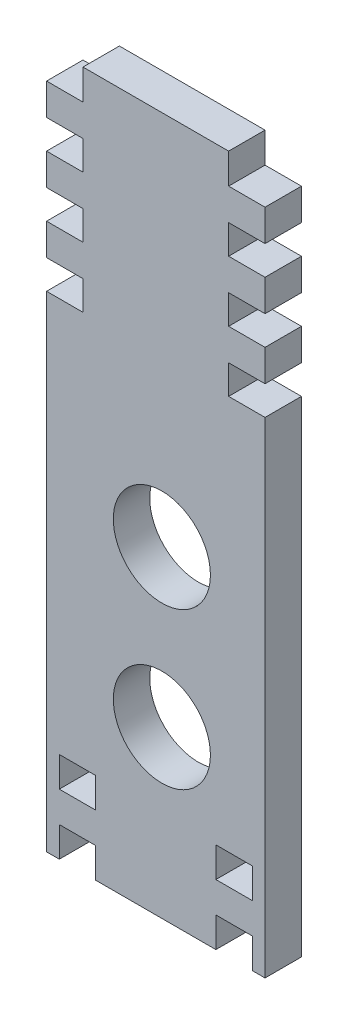
SolidWorks part; units mm, degrees
ref_plane "Plan de face" through (0, 0, 0) normal (0, 0, 1) x (1, 0, 0)
ref_plane "Plan de dessus" through (0, 0, 0) normal (0, 1, 0) x (1, 0, 0)
ref_plane "Plan de droite" through (0, 0, 0) normal (1, 0, 0) x (0, 0, -1)
sketch "Esquisse1" plane through (0, 0, 0) normal (0, 0, 1) x (1, 0, 0)
  line L0 (-12, 0) -> (12, 0)
  line L1 (12, 0) -> (12, -0.2)
  line L2 (12, -5) -> (18, -5)
  line L3 (18, -5) -> (18, -10.2)
  line L4 (18, -10.2) -> (12, -10.2)
  line L5 (12, -0.2) -> (12, -5)
  line L6 (0, 0) -> (0, -26.7853) construction
  line L7 (12, -10.2) -> (12, -15)
  line L8 (12, -15) -> (18, -15)
  line L9 (18, -15) -> (18, -20.2)
  line L10 (18, -20.2) -> (12, -20.2)
  line L11 (12, -20.2) -> (12, -25)
  line L12 (12, -25) -> (18, -25)
  line L13 (18, -25) -> (18, -30.2)
  line L14 (18, -30.2) -> (12, -30.2)
  line L15 (12, -30.2) -> (12, -35)
  line L16 (12, -35) -> (18, -35)
  line L22 (-12, -35) -> (-18, -35)
  line L23 (-12, -30.2) -> (-12, -35)
  line L24 (-18, -30.2) -> (-12, -30.2)
  line L25 (-18, -25) -> (-18, -30.2)
  line L26 (-12, -25) -> (-18, -25)
  line L27 (-12, -20.2) -> (-12, -25)
  line L28 (-18, -20.2) -> (-12, -20.2)
  line L29 (-18, -15) -> (-18, -20.2)
  line L30 (-12, -15) -> (-18, -15)
  line L31 (-12, -10.2) -> (-12, -15)
  line L32 (-12, -0.2) -> (-12, -5)
  line L33 (-18, -10.2) -> (-12, -10.2)
  line L34 (-18, -5) -> (-18, -10.2)
  line L35 (-12, -5) -> (-18, -5)
  line L36 (-12, 0) -> (-12, -0.2)
  line L46 (-18, -35) -> (-18, -115)
  line L47 (18, -40.2) -> (12, -40.2) [skipped]
  line L48 (-18, -115) -> (-15.9, -115)
  line L49 (18, -115) -> (18, -35)
  line L50 (0, -65) -> (0, 28.2086) construction
  line L51 (-15.9, -100.05) -> (-9.9, -100.05)
  line L52 (-15.9, -100.05) -> (-15.9, -105)
  line L53 (18, -35) -> (18, -40.2) [skipped]
  line L54 (-15.9, -105) -> (-9.9, -105)
  line L55 (-9.9, -100.05) -> (-9.9, -105)
  line L56 (-15.9, -110.05) -> (-9.9, -110.05)
  line L57 (-15.9, -110.05) -> (-15.9, -115)
  line L59 (-9.9, -110.05) -> (-9.9, -115)
  line L60 (-9.9, -115) -> (9.9, -115)
  line L61 (15.9, -110.05) -> (15.9, -115)
  line L62 (15.9, -110.05) -> (9.9, -110.05)
  line L63 (9.9, -110.05) -> (9.9, -115)
  line L64 (15.9, -105) -> (9.9, -105)
  line L65 (9.9, -100.05) -> (9.9, -105)
  line L66 (15.9, -100.05) -> (9.9, -100.05)
  line L67 (15.9, -100.05) -> (15.9, -105)
  line L68 (15.9, -115) -> (18, -115)
  circle A1 centre (1, -87.7) radius 8
  circle A2 centre (1, -62) radius 8
  point P8 (12, -0.2)
  point P41 (-12, -0.2)
  dimension "D7" = 16
  dimension "D8" = 11
  dimension "D9" = 62
  dimension "D10" = 25.7
  dimension "D11" = 16
  dimension "D1" = 5.2
  dimension "D2" = 0.2
  dimension "D3" = 4.8
  dimension "D4" = 6
  dimension "D5" = 24
  dimension "D14" = 5.05
  dimension "D15" = 4.95
  dimension "D12" = 80
  dimension "D13" = 4.95
  dimension "D17" = 6
  dimension "D18" = 6
  dimension "D19" = 9.9
  dimension "D20" = 9.9
  dimension "D6" = 4
extrude "Boss.-Extru.1" add sketch "Esquisse1" along normal blind 6
